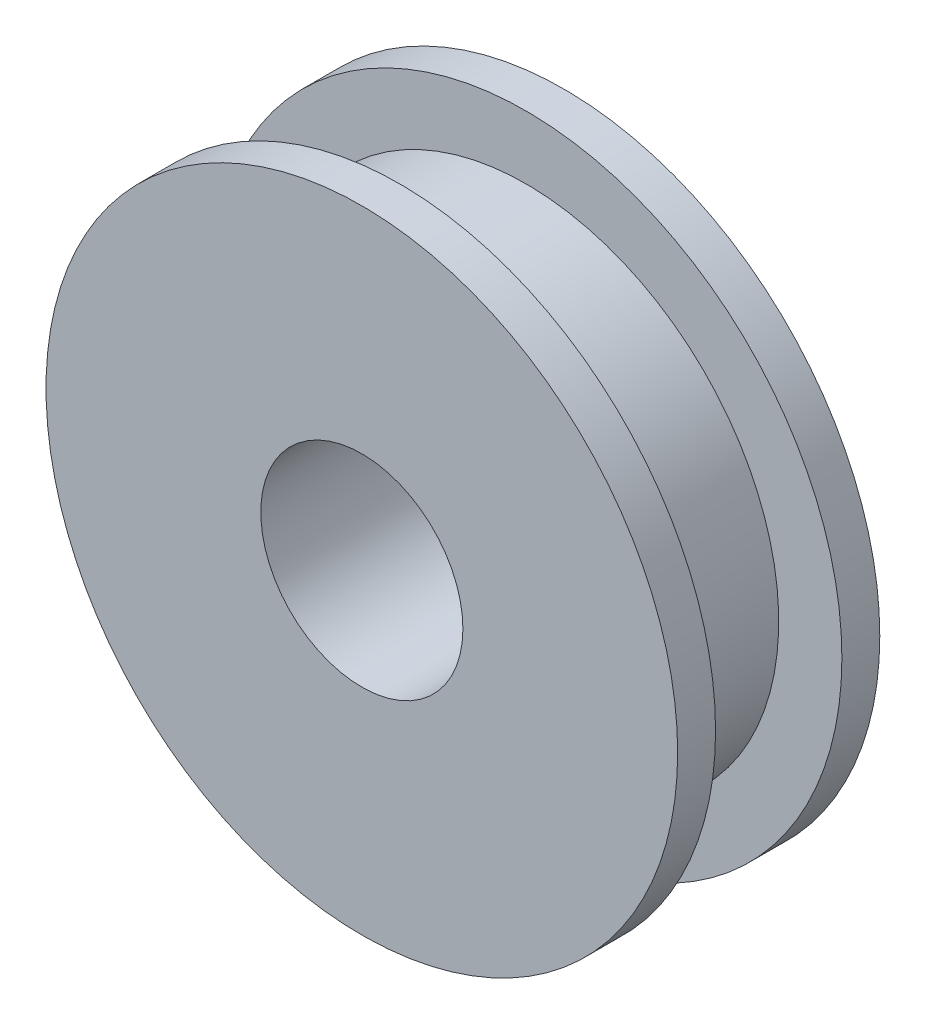
SolidWorks part; units mm, degrees
ref_plane "Alzado" through (0, 0, 0) normal (0, 0, 1) x (1, 0, 0)
ref_plane "Planta" through (0, 0, 0) normal (0, 1, 0) x (1, 0, 0)
ref_plane "Vista lateral" through (0, 0, 0) normal (1, 0, 0) x (0, 0, -1)
sketch "Croquis1" plane through (0, 0, 0) normal (0, 0, 1) x (1, 0, 0)
  circle A0 centre (0, 0) radius 8
  circle A1 centre (0, 0) radius 20
  dimension "D1" = 16
  dimension "D2" = 40
extrude "Saliente-Extruir1" add sketch "Croquis1" along normal mid plane 10
sketch "Croquis2" plane through (0, 0, 5) normal (0, 0, 1) x (1, 0, 0)
  circle A0 centre (0, 0) radius 8
  circle A1 centre (0, 0) radius 25
extrude "Saliente-Extruir2" add sketch "Croquis2" along normal blind 3
mirror "Simetría1" about plane through (0, 0, 0) normal (0, 0, 1) of "Saliente-Extruir2"
